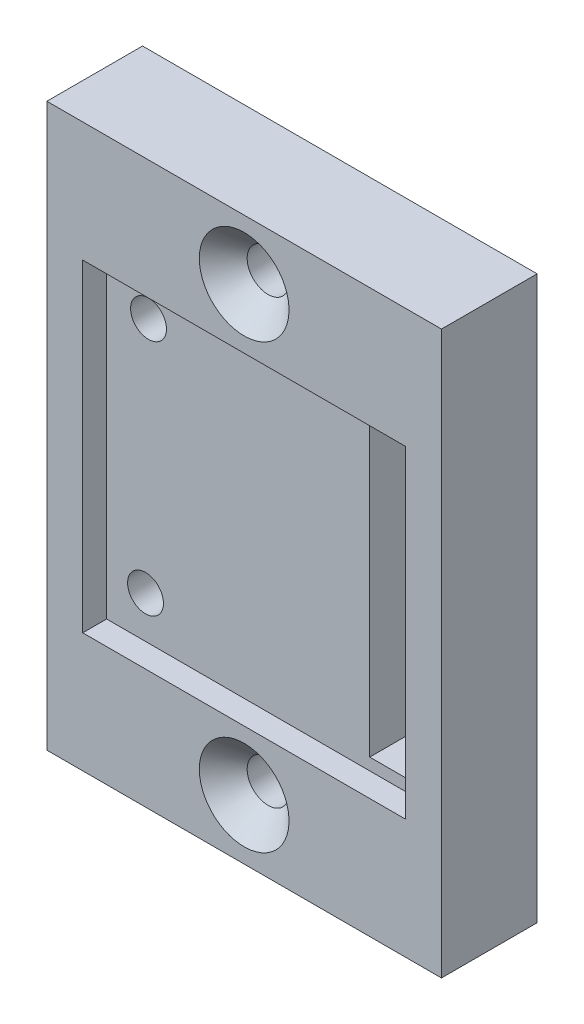
SolidWorks part; units mm, degrees
ref_plane "Front Plane" through (0, 0, 0) normal (0, 0, 1) x (1, 0, 0)
ref_plane "Top Plane" through (0, 0, 0) normal (0, 1, 0) x (1, 0, 0)
ref_plane "Right Plane" through (0, 0, 0) normal (1, 0, 0) x (0, 0, -1)
sketch "Sketch1" plane through (0, 0, 0) normal (0, 0, 1) x (1, 0, 0)
  line L1 (0, 0) -> (33, 0)
  line L2 (0, 0) -> (0, 47)
  line L3 (0, 47) -> (33, 47)
  line L4 (33, 0) -> (33, 47)
  line L5 (3, 37) -> (30, 37)
  line L6 (3, 37) -> (3, 10)
  line L7 (3, 10) -> (30, 10)
  line L8 (30, 37) -> (30, 10)
  circle A0 centre (16.5, 42) radius 1.75
  circle A1 centre (16.5, 5) radius 1.75
  dimension "D8" = 16.5
  dimension "D9" = 3.5
  dimension "D10" = 3.5
  dimension "D11" = 5
  dimension "D12" = 5
  dimension "D1" = 27
  dimension "D2" = 27
  dimension "D3" = 10
  dimension "D4" = 10
  dimension "D5" = 3
  dimension "D6" = 3
  dimension "D7" = 16.5
extrude "Boss-Extrude1" add sketch "Sketch1" along normal blind 8
sketch "Sketch3" plane through (0, 0, 0) normal (0, 0, -1) x (-1, 0, 0)
  line L1 (-30, 37) -> (-3, 37)
  line L2 (-30, 37) -> (-30, 10)
  line L3 (-30, 10) -> (-3, 10)
  line L4 (-3, 37) -> (-3, 10)
extrude "Boss-Extrude2" add sketch "Sketch3" against normal blind 6
chamfer "Chamfer1" distance 2 angle 45 2 edges at (18.25, 5, 8) (18.25, 42, 8)
sketch "Sketch4" plane through (0, 0, 6) normal (0, 0, 1) x (1, 0, 0)
  line L0 (3, 10) -> (3, 37) construction
  line L1 (3, 37) -> (30, 37) construction
  circle A0 centre (6.5, 33.5) radius 1.5
  circle A1 centre (6.25, 13.5016) radius 1.5
  dimension "D1" = 20
  dimension "D2" = 3.25
  dimension "D3" = 3.5
  dimension "D4" = 3.5
  dimension "D5" = 3
  dimension "D6" = 3
extrude "Cut-Extrude1" cut sketch "Sketch4" against normal blind 10
sketch "Sketch5" plane through (0, 0, 6) normal (0, 0, 1) x (1, 0, 0)
  line L0 (30, 37) -> (3, 37) construction
  line L1 (29, 36) -> (25, 36)
  line L2 (29, 36) -> (29, 11)
  line L3 (29, 11) -> (25, 11)
  line L4 (25, 36) -> (25, 11)
  line L5 (30, 37) -> (30, 10) construction
  line L6 (3, 10) -> (30, 10) construction
  point P8 (27, 11)
  dimension "D1" = 4
  dimension "D2" = 1
  dimension "D3" = 1
  dimension "D4" = 1
extrude "Cut-Extrude2" cut sketch "Sketch5" against normal blind 3
sketch "Sketch6" plane through (0, 0, 0) normal (0, 0, -1) x (-1, 0, 0)
  line L1 (-6.5, 36.9641) -> (-9.5, 35.2321)
  line L2 (-9.5, 35.2321) -> (-9.5, 31.7679)
  line L3 (-9.5, 31.7679) -> (-6.5, 30.0359)
  line L4 (-6.5, 30.0359) -> (-3.5, 31.7679)
  line L5 (-3.5, 31.7679) -> (-3.5, 35.2321)
  line L6 (-3.5, 35.2321) -> (-6.5, 36.9641)
  line L7 (-3.25, 15.2336) -> (-6.25, 16.9657)
  line L8 (-6.25, 16.9657) -> (-9.25, 15.2336)
  line L9 (-9.25, 15.2336) -> (-9.25, 11.7695)
  line L10 (-9.25, 11.7695) -> (-6.25, 10.0375)
  line L11 (-6.25, 10.0375) -> (-3.25, 11.7695)
  line L12 (-3.25, 11.7695) -> (-3.25, 15.2336)
  line L13 (0, 47) -> (0, 0) construction
  circle A0 centre (-6.5, 33.5) radius 3 construction
  circle A1 centre (-6.25, 13.5016) radius 3 construction
  point P10 (-7.75, 16.0996)
  dimension "D1" = 6
  dimension "D2" = 6
  dimension "D3" = 0
  dimension "D4" = 0
extrude "Cut-Extrude3" cut sketch "Sketch6" against normal blind 3
